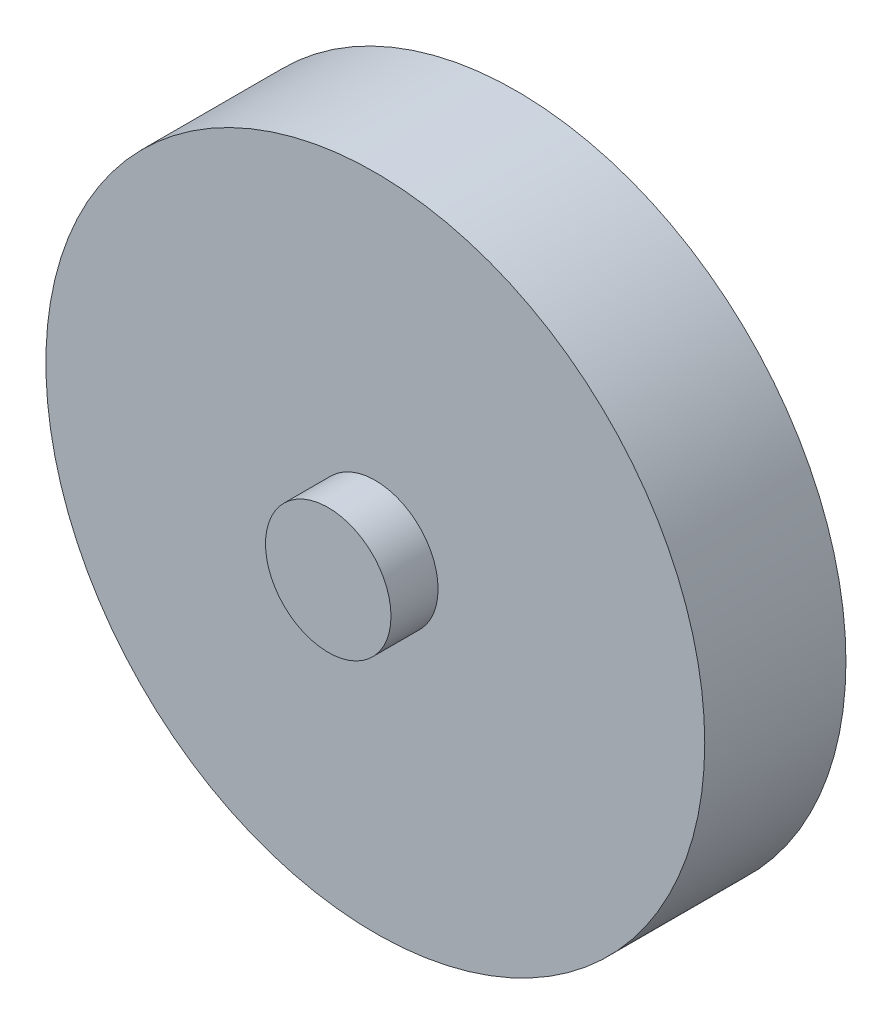
SolidWorks part; units mm, degrees
ref_plane "前视基准面" through (0, 0, 0) normal (0, 0, 1) x (1, 0, 0)
ref_plane "上视基准面" through (0, 0, 0) normal (0, 1, 0) x (1, 0, 0)
ref_plane "右视基准面" through (0, 0, 0) normal (1, 0, 0) x (0, 0, -1)
other "Configuration Table"
sketch "草图1" plane through (0, 0, 0) normal (0, 0, 1) x (1, 0, 0)
  circle A0 centre (0, 0) radius 8
extrude "凸台-拉伸1" add sketch "草图1" along normal blind 24
sketch "草图2" plane through (0, 0, 0) normal (0, 0, 1) x (1, 0, 0)
  circle A0 centre (0, 0) radius 42
extrude "凸台-拉伸2" add sketch "草图2" along normal blind 18
sketch "草图3" plane through (0, 0, 18) normal (0, 0, 1) x (1, 0, 0)
  line L0 (42, 0) -> (41.5984, 5.7942)
  line L1 (41.5984, 5.7942) -> (41.5912, 5.8153)
  line L2 (41.5912, 5.8153) -> (40.671, 5.8153)
  line L3 (40.671, 5.8153) -> (39.8432, 4.763)
  line L4 (39.8432, 4.763) -> (39.1199, 4.763)
  line L5 (39.1199, 4.763) -> (38.5116, 4.1707)
  line L6 (38.5116, 4.1707) -> (38.0276, 4.009)
  line L7 (38.0276, 4.009) -> (37.6754, 3.9151)
  line L8 (37.6754, 3.9151) -> (37.461, 3.8716)
  line L9 (37.461, 3.8716) -> (37.3458, 3.3974)
  line L10 (37.3458, 3.3974) -> (37.3844, 2.9422)
  line L11 (37.3844, 2.9422) -> (37.4175, 2.4866)
  line L12 (37.4175, 2.4866) -> (37.445, 2.0305)
  line L13 (37.445, 2.0305) -> (37.5326, 2.0353)
  line L14 (37.5326, 2.0353) -> (37.6055, 2.0362)
  line L15 (37.6055, 2.0362) -> (37.824, 2.0269)
  line L16 (37.824, 2.0269) -> (38.1865, 1.9892)
  line L17 (38.1865, 1.9892) -> (38.6899, 1.9052)
  line L18 (38.6899, 1.9052) -> (39.3292, 1.7573)
  line L19 (39.3292, 1.7573) -> (39.8432, 1.7573)
  line L20 (39.8432, 1.7573) -> (41.5984, 1.7573)
  circle A0 centre (0, 0) radius 42 construction
